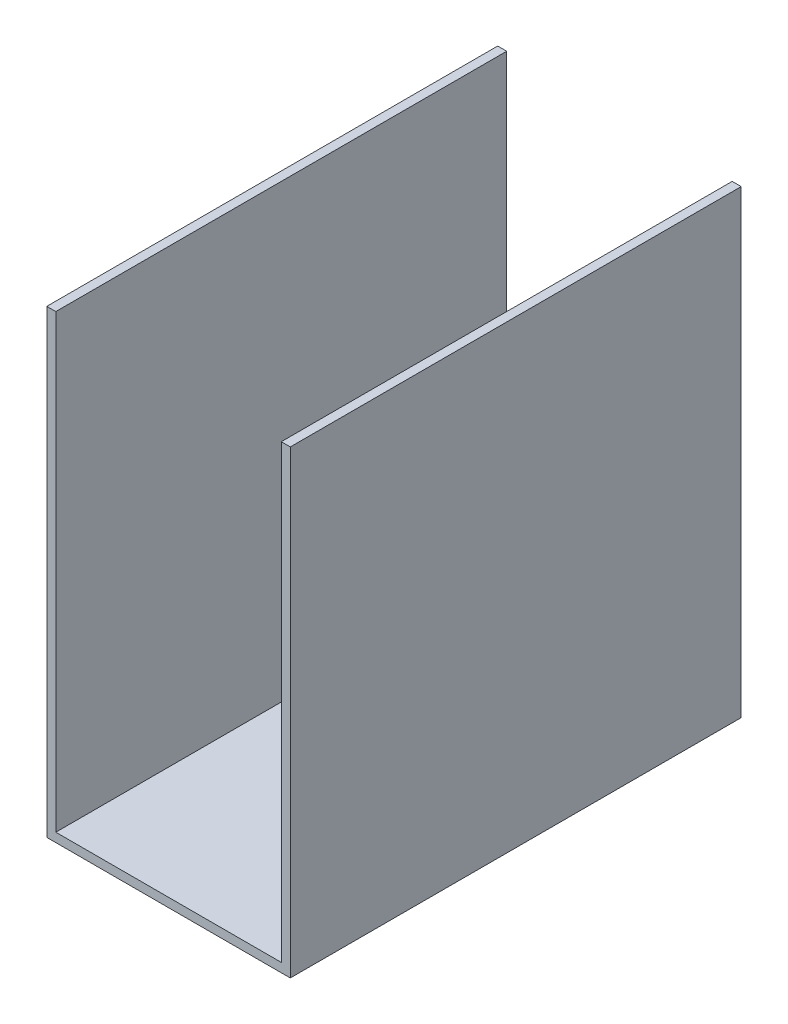
SolidWorks part; units mm, degrees
ref_plane "Front Plane" through (0, 0, 0) normal (0, 0, 1) x (1, 0, 0)
ref_plane "Top Plane" through (0, 0, 0) normal (0, 1, 0) x (1, 0, 0)
ref_plane "Right Plane" through (0, 0, 0) normal (1, 0, 0) x (0, 0, -1)
sketch "Sketch2" plane through (0, 0, 0) normal (0, 0, 1) x (1, 0, 0)
  line L0 (0, 0) -> (0, -10000)
  line L1 (0, -10000) -> (5000, -10000)
  line L2 (5000, -10000) -> (5000, 0)
  line L3 (-200, 0) -> (-200, -10200)
  line L4 (-200, -10200) -> (5200, -10200)
  line L5 (5200, -10200) -> (5200, 0)
  line L6 (-200, 0) -> (0, 0)
  line L7 (5000, 0) -> (5200, 0)
extrude "Boss-Extrude1" add sketch "Sketch2" against normal blind 10000
